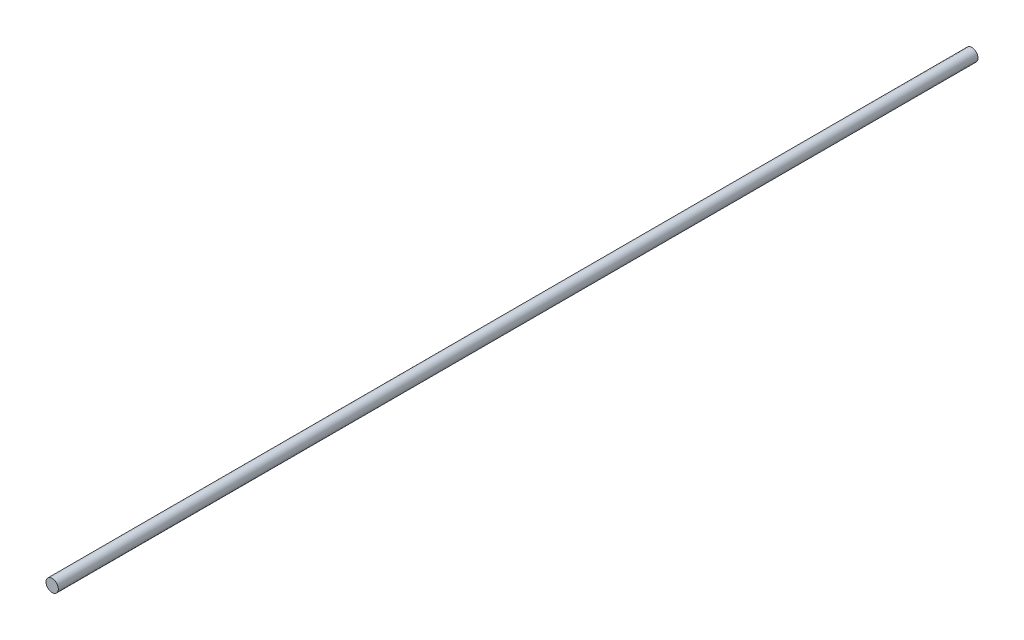
SolidWorks part; units mm, degrees
material "Pine"
ref_plane "Front Plane" through (0, 0, 0) normal (0, 0, 1) x (1, 0, 0)
ref_plane "Top Plane" through (0, 0, 0) normal (0, 1, 0) x (1, 0, 0)
ref_plane "Right Plane" through (0, 0, 0) normal (1, 0, 0) x (0, 0, -1)
sketch "Sketch1" plane through (0, 0, 0) normal (0, 0, 1) x (1, 0, 0)
  circle A0 centre (0, 0) radius 2.3813
  dimension "D1" = 4.7625
extrude "Boss-Extrude1" add sketch "Sketch1" along normal mid plane 355.6
